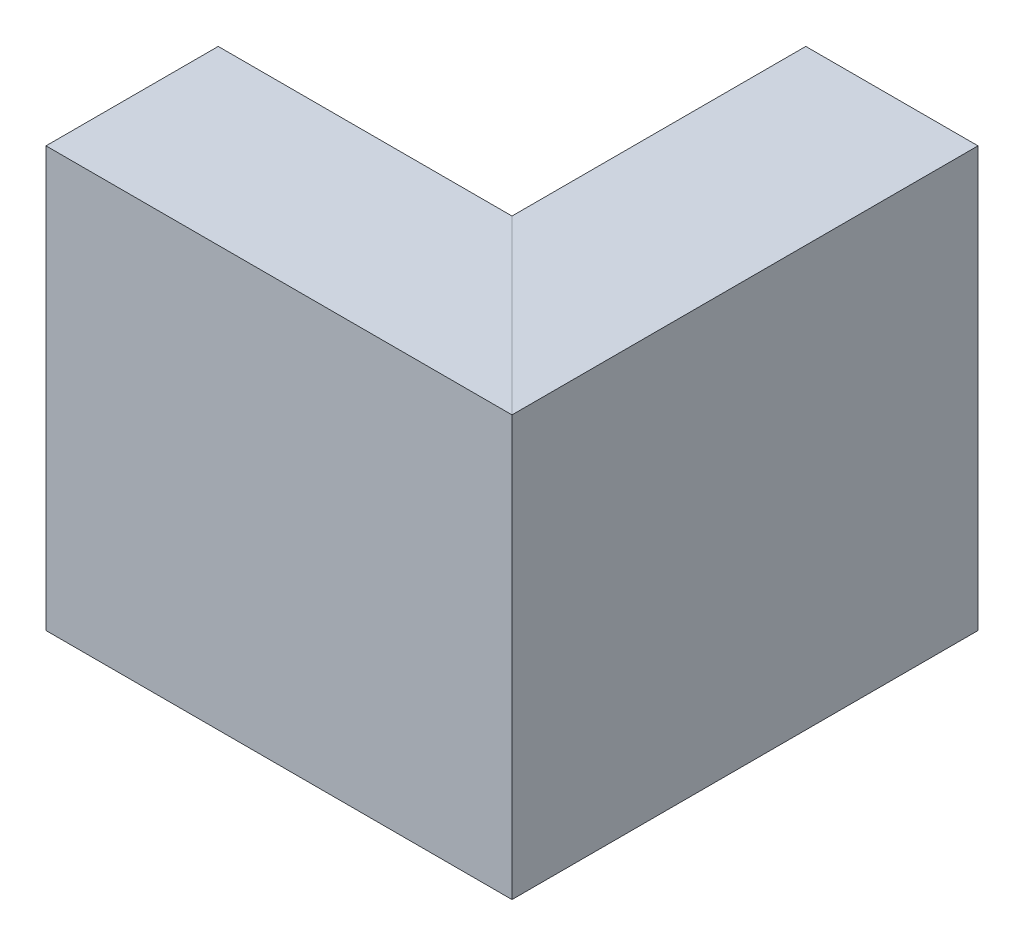
SolidWorks part; units mm, degrees
ref_plane "Front Plane" through (0, 0, 0) normal (0, 0, 1) x (1, 0, 0)
ref_plane "Top Plane" through (0, 0, 0) normal (0, 1, 0) x (1, 0, 0)
ref_plane "Right Plane" through (0, 0, 0) normal (1, 0, 0) x (0, 0, -1)
sketch "Sketch1" plane through (0, 0, 0) normal (0, 0, 1) x (1, 0, 0)
  line L0 (2.3178, -19.05) -> (4.3178, -19.05)
  line L1 (4.3178, -19.05) -> (4.3178, 2)
  line L2 (4.3178, 2) -> (-4.3178, 2)
  line L3 (-4.3178, 2) -> (-3.1872, -22.225)
  line L4 (-3.1872, -22.225) -> (-1.2806, -22.225)
  line L5 (-1.2806, -22.225) -> (-2.3177, 0)
  line L6 (-2.3177, 0) -> (2.3177, 0)
  line L7 (2.3177, 0) -> (2.3178, -19.05)
  line L8 (0, 0) -> (0, 2) construction
  line L9 (-1.4287, -19.05) -> (2.3178, -19.05) construction
  point P12 (0, 0)
  dimension "D1" = 2
  dimension "D2" = 2
  dimension "D3" = 4.6355
  dimension "D5" = 19.05
  dimension "D4" = 3.7465
  dimension "D6" = 3.175
sketch "Sketch2" plane through (0, 0, 0) normal (0, 1, 0) x (1, 0, 0)
  line L0 (0, 0) -> (0, -19.05)
  line L1 (0, -19.05) -> (-19.05, -19.05)
  dimension "D1" = 19.05
  dimension "D2" = 19.05
sweep "Sweep1" add profiles "Sketch1" path "Sketch2"
sketch "Sketch3" plane through (0, 0, 0) normal (0, -1, 0) x (1, 0, 0)
  line L0 (2.3178, 21.3677) -> (-2.3177, 16.7322) construction
  line L1 (-5.3178, 13.7322) -> (-1.2806, 13.7322)
  line L2 (-5.3178, 13.7322) -> (-5.3178, 17.7694)
  line L3 (-5.3178, 17.7694) -> (-1.2806, 17.7694)
  line L4 (-1.2806, 13.7322) -> (-1.2806, 17.7694)
  line L5 (-1.2806, 17.7694) -> (-3.1872, 15.8628) construction
  line L6 (-1.2806, 0) -> (-1.2806, 17.7694) construction
  line L8 (-4.3178, 14.7322) -> (-19.05, 14.7322) construction
  dimension "D1" = 1
extrude "Cut-Extrude1" cut sketch "Sketch3" along normal through all
equation "\"Height\"= 12in"
equation "\"Depth\"= 7in"
equation "\"WallThickness\"= 0.1875in"
equation "\"FloorThickness\"= 0.1875in"
equation "\"Width\" = 30in"
equation "\"D3@Sketch1\"=\"WallThickness\"-.005"
equation "\"D4@Sketch1\"=\"WallThickness\"-.04in"
